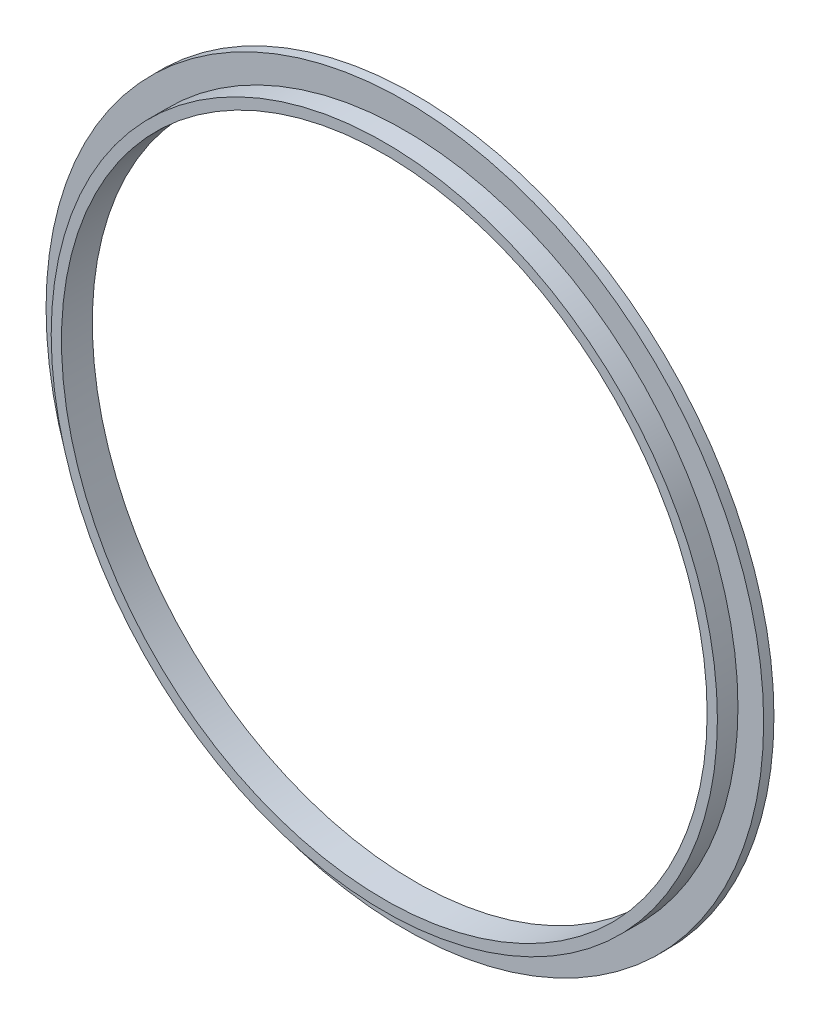
SolidWorks part; units mm, degrees
ref_plane "Front Plane" through (0, 0, 0) normal (0, 0, 1) x (1, 0, 0)
ref_plane "Top Plane" through (0, 0, 0) normal (0, 1, 0) x (1, 0, 0)
ref_plane "Right Plane" through (0, 0, 0) normal (1, 0, 0) x (0, 0, -1)
sketch "Sketch1" plane through (0, 0, 0) normal (0, 0, 1) x (1, 0, 0)
  circle A0 centre (0, 0) radius 69.8
  circle A1 centre (0, 0) radius 62.8
  dimension "D1" = 7
  dimension "D2" = 125.6
extrude "Boss-Extrude1" add sketch "Sketch1" along normal blind 2
sketch "Sketch2" plane through (0, 0, 2) normal (0, 0, 1) x (1, 0, 0)
  circle A0 centre (0, 0) radius 62.8 construction
  circle A1 centre (0, 0) radius 62.8
  circle A2 centre (0, 0) radius 64.8
  dimension "D1" = 2
extrude "Boss-Extrude2" add sketch "Sketch2" along normal blind 4
